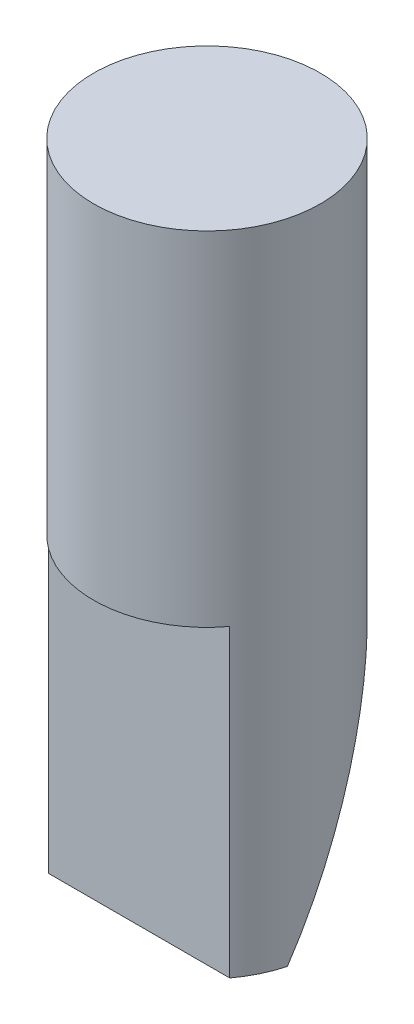
SolidWorks part; units mm, degrees
ref_plane "Ebene vorne" through (0, 0, 0) normal (0, 0, 1) x (1, 0, 0)
ref_plane "Ebene oben" through (0, 0, 0) normal (0, 1, 0) x (1, 0, 0)
ref_plane "Ebene rechts" through (0, 0, 0) normal (1, 0, 0) x (0, 0, -1)
sketch "Skizze1" plane through (0, 0, 0) normal (0, 1, 0) x (1, 0, 0)
  circle A0 centre (0, 0) radius 17.5
  dimension "D1" = 35
extrude "Aufsatz-Linear austragen1" add sketch "Skizze1" along normal blind 100
sketch "Skizze2" plane through (0, 0, 0) normal (1, 0, 0) x (0, 0, -1)
  line L0 (-17.5, 0) -> (-17.5, 47)
  line L1 (-17.5, 100) -> (-17.5, 0) construction
  line L2 (-17.5, 47) -> (-10.5, 47)
  line L3 (-10.5, 47) -> (-10.5, 0)
  line L4 (-17.5, 0) -> (17.5, 0) construction
  line L5 (-10.5, 0) -> (-17.5, 0)
  line L6 (-4.5, 0) -> (17.5, 47)
  line L7 (17.5, 0) -> (17.5, 100) construction
  line L8 (17.5, 47) -> (17.5, 0)
  line L9 (17.5, 0) -> (-4.5, 0)
  line L10 (-10.5, 47) -> (17.5, 47) construction
  line L11 (17.5, 100) -> (-17.5, 100) construction
  dimension "D1" = 53
  dimension "D2" = 7
  dimension "D3" = 6
extrude "Schnitt-Linear austragen1" cut sketch "Skizze2" against normal through all both and the other way through all
